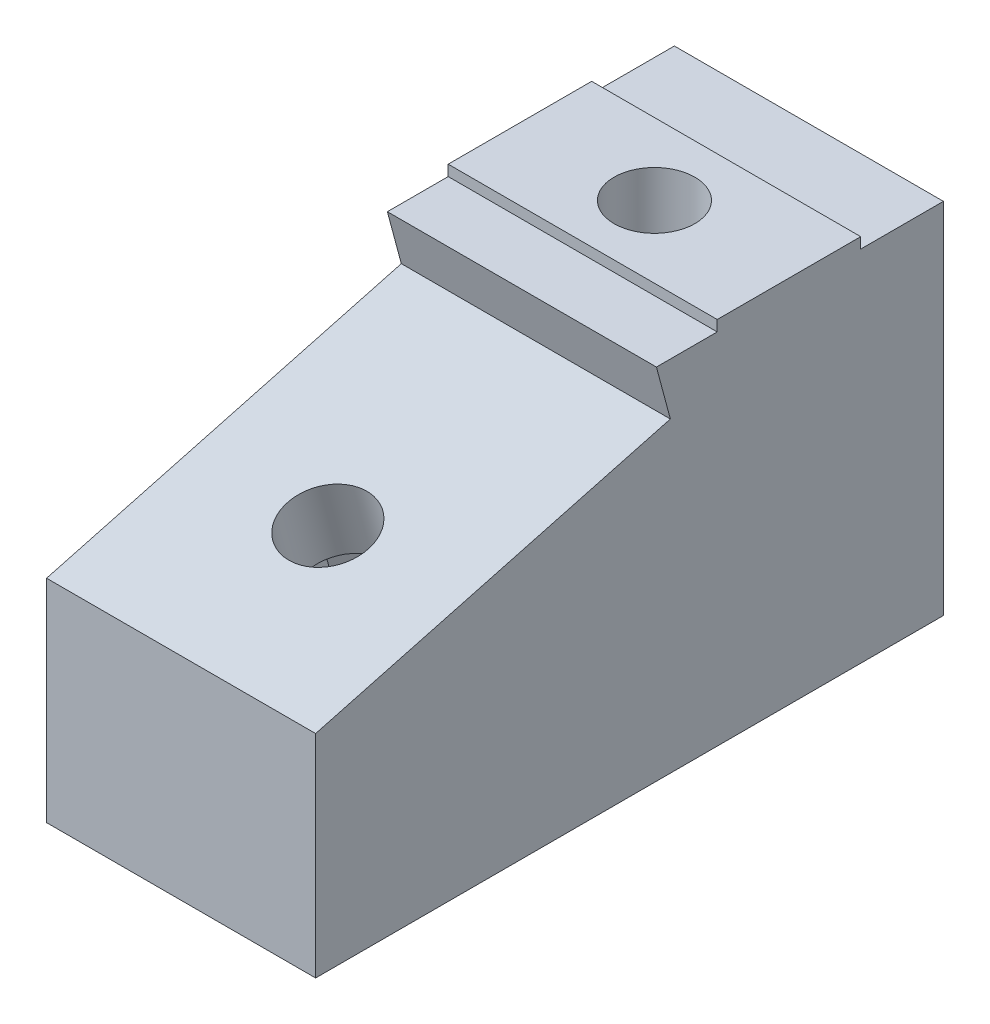
SolidWorks part; units mm, degrees
material "3D printed plastic"
ref_plane "Front Plane" through (0, 0, 0) normal (0, 0, 1) x (1, 0, 0)
ref_plane "Top Plane" through (0, 0, 0) normal (0, 1, 0) x (1, 0, 0)
ref_plane "Right Plane" through (0, 0, 0) normal (1, 0, 0) x (0, 0, -1)
sketch "Sketch1" plane through (0, 0, 0) normal (1, 0, 0) x (0, 0, -1)
  line L0 (0.7765, -2.8978) -> (-19, -8.1969)
  line L1 (-19, -8.1969) -> (-19, -20)
  line L2 (-19, -20) -> (16, -20)
  line L3 (16, -20) -> (16, 0)
  line L4 (16, 0) -> (0, 0)
  line L5 (0.7765, -2.8978) -> (0, 0)
  dimension "D1" = 15
  dimension "D2" = 3
  dimension "D3" = 16
  dimension "D4" = 20
  dimension "D5" = 35
extrude "Boss-Extrude1" add sketch "Sketch1" along normal mid plane 15
sketch "Sketch2" plane through (0, -2.8978, -0.7765) normal (0, 0.9659, 0.2588) x (1, 0, 0)
  line L0 (0, 11.1962) -> (0, -12.0038) construction
  line L1 (7.5, 11.1962) -> (-7.5, 11.1962) construction
  circle A0 centre (0, -12.0038) radius 2.25
  dimension "D1" = 4.5
  dimension "D2" = 23.2
extrude "Cut-Extrude1" cut sketch "Sketch2" against normal through all
sketch "Sketch3" plane through (0, -20, 0) normal (0, -1, 0) x (1, 0, 0)
  line L0 (0, -7.39) -> (0, -16) construction
  line L1 (7.5, -16) -> (-7.5, -16) construction
  circle A0 centre (0, -7.39) radius 2.25
  dimension "D1" = 4.5
  dimension "D2" = 7.39
extrude "Cut-Extrude2" cut sketch "Sketch3" against normal through all
sketch "Sketch4" plane through (0, -2.8978, -0.7765) normal (0, 0.9659, 0.2588) x (1, 0, 0)
  line L1 (0, -16.103) -> (3.55, -14.0534)
  line L2 (3.55, -14.0534) -> (3.55, -9.9543)
  line L3 (3.55, -9.9543) -> (0, -7.9047)
  line L4 (0, -7.9047) -> (-3.55, -9.9543)
  line L5 (-3.55, -9.9543) -> (-3.55, -14.0534)
  line L6 (-3.55, -14.0534) -> (0, -16.103)
  circle A0 centre (0, -12.0038) radius 3.55 construction
  dimension "D1" = 7.1
extrude "Cut-Extrude3" cut sketch "Sketch4" against normal through all from offset 4 offset against normal yes
sketch "Sketch5" plane through (0, 0, 0) normal (0, 1, 0) x (1, 0, 0)
  line L0 (-7.5, 16) -> (-7.5, 0) construction
  line L1 (-7.5, 11.39) -> (7.5, 11.39)
  line L2 (-7.5, 11.39) -> (-7.5, 3.39)
  line L3 (-7.5, 3.39) -> (7.5, 3.39)
  line L4 (7.5, 11.39) -> (7.5, 3.39)
  line L5 (7.5, 16) -> (7.5, 0) construction
  line L6 (0, 7.39) -> (7.5, 7.39) construction
  circle A0 centre (0, 7.39) radius 2.25
  circle A1 centre (0, 7.39) radius 2.25 construction
  dimension "D1" = 8
extrude "Boss-Extrude2" add sketch "Sketch5" along normal blind 0.6
sketch "Sketch6" plane through (0, -20, 0) normal (0, -1, 0) x (1, 0, 0)
  circle A0 centre (0, -7.39) radius 5
  dimension "D1" = 10
extrude "Cut-Extrude4" cut sketch "Sketch6" against normal blind 8
